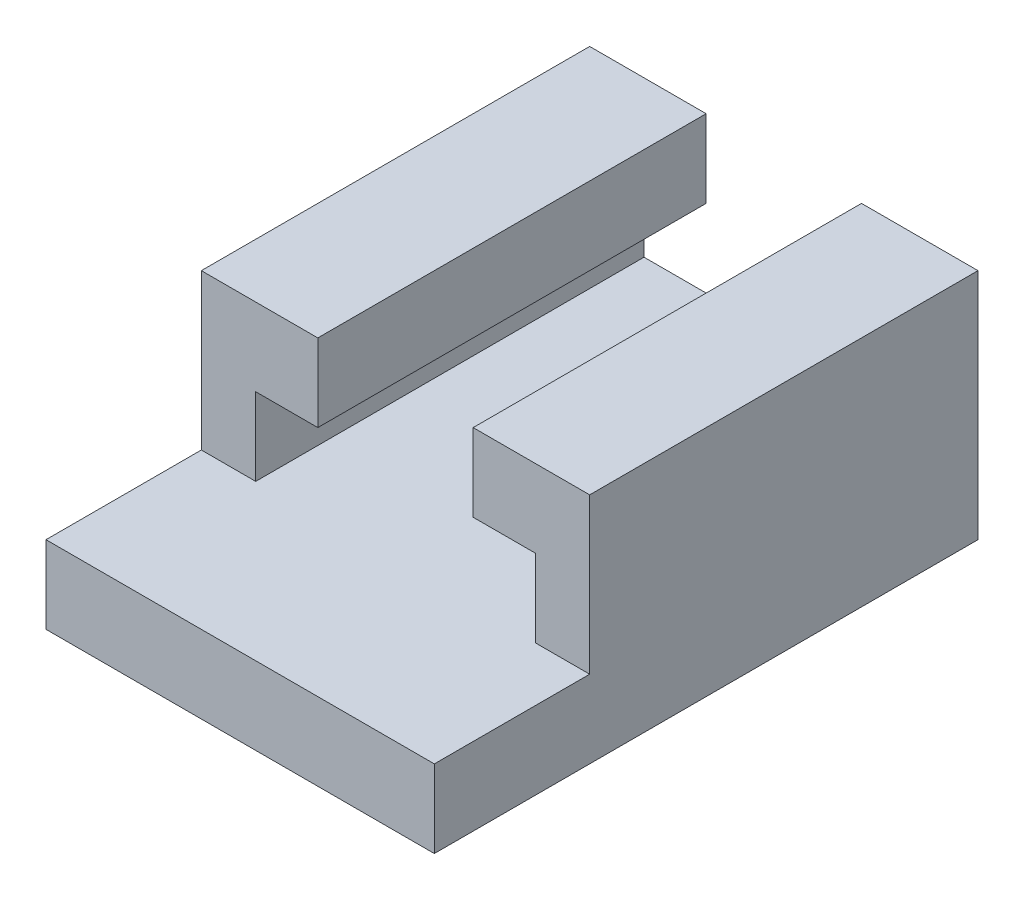
SolidWorks part; units mm, degrees
ref_plane "Front Plane" through (0, 0, 0) normal (0, 0, 1) x (1, 0, 0)
ref_plane "Top Plane" through (0, 0, 0) normal (0, 1, 0) x (1, 0, 0)
ref_plane "Right Plane" through (0, 0, 0) normal (1, 0, 0) x (0, 0, -1)
sketch "Sketch1" plane through (0, 0, 0) normal (0, 1, 0) x (1, 0, 0)
  line L1 (-0.6173, 1.8518) -> (4.3827, 1.8518)
  line L2 (-0.6173, 1.8518) -> (-0.6173, 8.8518)
  line L3 (-0.6173, 8.8518) -> (4.3827, 8.8518)
  line L4 (4.3827, 1.8518) -> (4.3827, 8.8518)
extrude "Boss-Extrude1" add sketch "Sketch1" along normal blind 3 contours L3 L4 L1 L2
sketch "Sketch2" plane through (0, 3, 0) normal (0, 1, 0) x (1, 0, 0)
  line L0 (4.3827, 1.8518) -> (4.3827, 8.8518) construction
  line L1 (0.8827, 8.8518) -> (2.8827, 8.8518)
  line L2 (0.8827, 8.8518) -> (0.8827, 1.8518)
  line L3 (0.8827, 1.8518) -> (2.8827, 1.8518)
  line L4 (2.8827, 8.8518) -> (2.8827, 1.8518)
  line L5 (-0.6173, 1.8518) -> (-0.6173, 8.8518) construction
  line L6 (-0.6173, 8.8518) -> (4.3827, 8.8518) construction
  line L7 (-0.6173, 1.8518) -> (4.3827, 1.8518) construction
  dimension "D1" = 1.5
  dimension "D2" = 1.5
  dimension "D3" = 2
extrude "Cut-Extrude1" cut sketch "Sketch2" against normal blind 2
sketch "Sketch3" plane through (0, 0, -8.8518) normal (0, 0, -1) x (-1, 0, 0)
  line L0 (-4.3827, 3) -> (-4.3827, 0) construction
  line L1 (-3.6827, 2) -> (-0.0827, 2)
  line L2 (-3.6827, 2) -> (-3.6827, 1)
  line L3 (-3.6827, 1) -> (-0.0827, 1)
  line L4 (-0.0827, 2) -> (-0.0827, 1)
  line L5 (0.6173, 3) -> (0.6173, 0) construction
  line L7 (-2.8827, 3) -> (-4.3827, 3) construction
  dimension "D1" = 0.7
  dimension "D2" = 0.7
  dimension "D3" = 1
  dimension "D4" = 2
extrude "Cut-Extrude2" cut sketch "Sketch3" against normal through all
sketch "Sketch4" plane through (0, 0, -1.8518) normal (0, 0, 1) x (1, 0, 0)
  line L1 (4.3827, 1) -> (-0.6173, 1)
  line L2 (4.3827, 1) -> (4.3827, 3)
  line L3 (4.3827, 3) -> (-0.6173, 3)
  line L4 (-0.6173, 1) -> (-0.6173, 3)
  line L5 (0.0827, 1) -> (3.6827, 1) construction
  line L6 (-0.6173, 3) -> (-0.6173, 0) construction
  line L7 (-0.6173, 3) -> (0.8827, 3) construction
  line L8 (4.3827, 3) -> (4.3827, 0) construction
extrude "Cut-Extrude3" cut sketch "Sketch4" against normal blind 2
